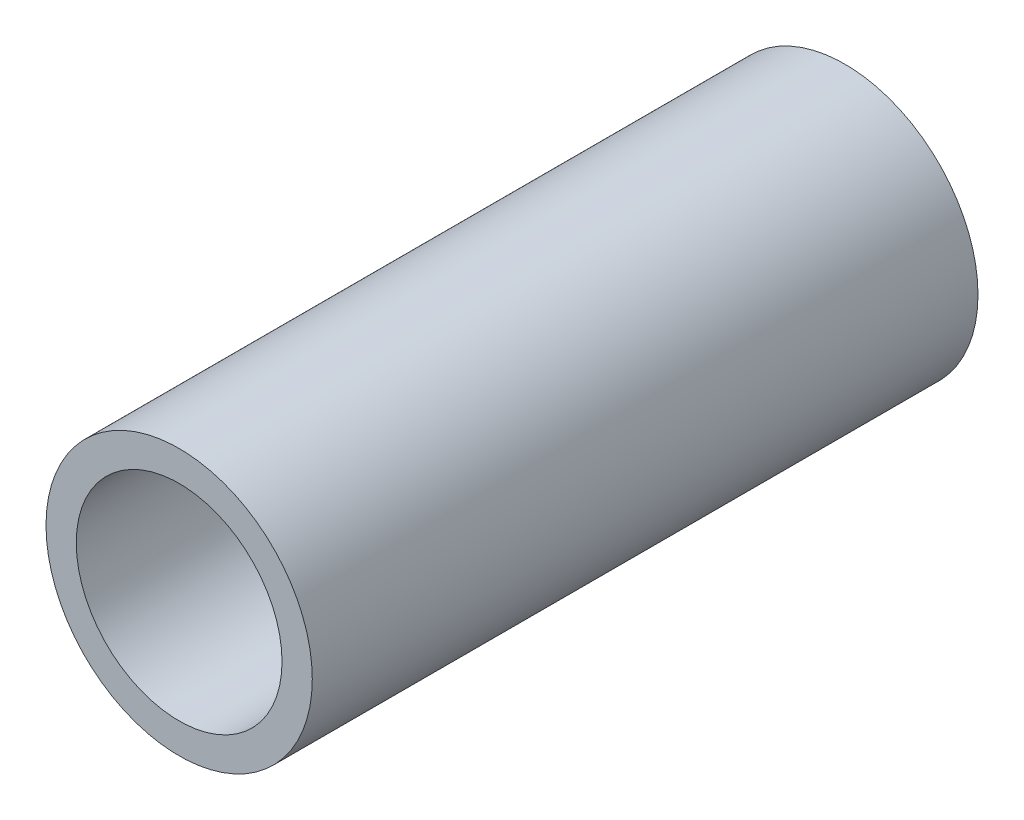
SolidWorks part; units mm, degrees
ref_plane "Front Plane" through (0, 0, 0) normal (0, 0, 1) x (1, 0, 0)
ref_plane "Top Plane" through (0, 0, 0) normal (0, 1, 0) x (1, 0, 0)
ref_plane "Right Plane" through (0, 0, 0) normal (1, 0, 0) x (0, 0, -1)
sketch "Sketch1" plane through (0, 0, 0) normal (0, 0, 1) x (1, 0, 0)
  circle A0 centre (0, 0) radius 1.7
  circle A1 centre (0, 0) radius 2.2
  dimension "D1" = 3.4
  dimension "D2" = 4.4
extrude "Boss-Extrude1" add sketch "Sketch1" along normal blind 11
